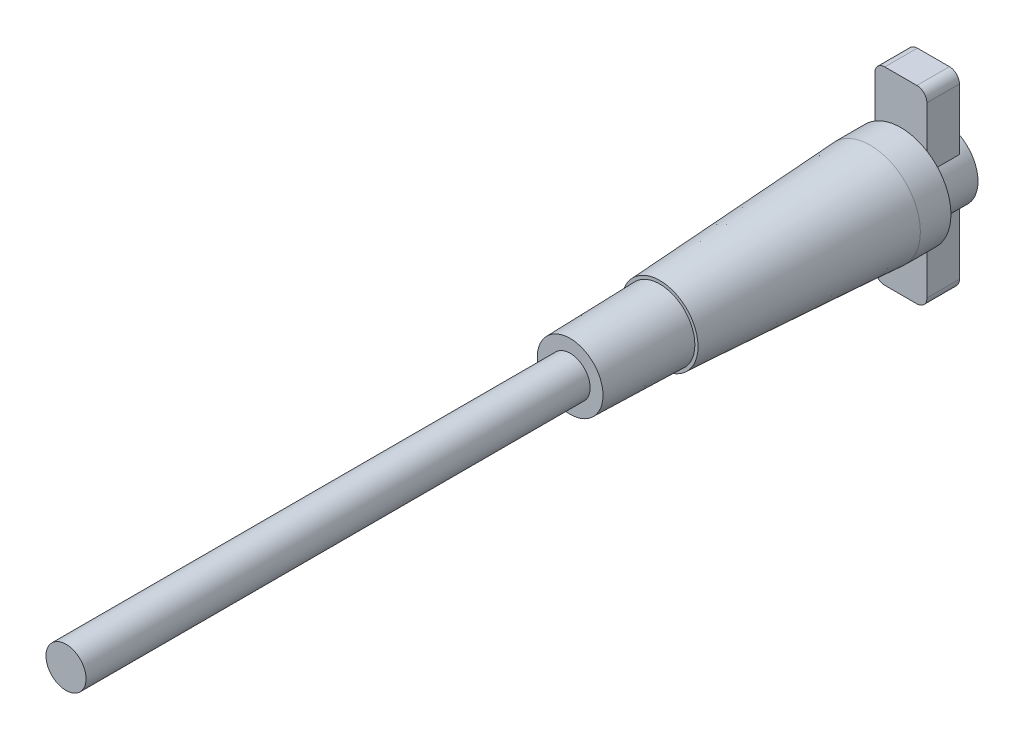
SolidWorks part; units mm, degrees
ref_plane "Front Plane" through (0, 0, 0) normal (0, 0, 1) x (1, 0, 0)
ref_plane "Top Plane" through (0, 0, 0) normal (0, 1, 0) x (1, 0, 0)
ref_plane "Right Plane" through (0, 0, 0) normal (1, 0, 0) x (0, 0, -1)
sketch "Sketch2" plane through (0, 0, 0) normal (1, 0, 0) x (0, 0, -1)
  line L0 (0, 3.556) -> (-4.2672, 3.556)
  line L1 (-4.2672, 3.556) -> (-4.2672, 5.08)
  line L2 (-4.2672, 5.08) -> (-7.366, 5.08)
  line L3 (-7.366, 5.08) -> (-28.702, 3.8735)
  line L4 (-28.702, 3.8735) -> (-28.702, 3.556)
  line L5 (-28.702, 3.556) -> (-37.7952, 3.3337)
  line L6 (-37.7952, 3.3337) -> (-37.7952, 2.032)
  line L7 (-37.7952, 2.032) -> (-88.9, 2.032)
  line L8 (-88.9, 2.032) -> (-88.9, 0)
  line L9 (-88.9, 0) -> (0, 0)
  line L10 (0, 0) -> (0, 3.556)
  point P12 (-46.6451, 2.8937)
  point P13 (-102.8631, 3.8506)
  point P14 (-102.8107, 4.607)
  point P15 (-8.9365, 5.08)
  point P16 (-4.2672, 3.1117)
  dimension "D1" = 4.2672
  dimension "D2" = 5.08
  dimension "D3" = 2.032
  dimension "D4" = 3.3337
  dimension "D5" = 3.556
  dimension "D6" = 3.8735
  dimension "D7" = 28.702
  dimension "D8" = 7.366
  dimension "D9" = 37.7952
  dimension "D10" = 3.556
  dimension "D11" = 88.9
revolve "Revolve1" add sketch "Sketch2" angle 360 about L9
sketch "Sketch3" plane through (0, 0, 4.2672) normal (0, 0, -1) x (-1, 0, 0)
  line L1 (-1.6256, -9.5885) -> (1.6256, -9.5885)
  line L2 (-2.6416, -8.5725) -> (-2.6416, 8.5725)
  line L3 (-1.6256, 9.5885) -> (1.6256, 9.5885)
  line L4 (2.6416, -8.5725) -> (2.6416, 8.5725)
  line L5 (-2.6416, -9.5885) -> (2.6416, 9.5885) construction
  line L6 (-2.6416, 9.5885) -> (2.6416, -9.5885) construction
  arc A0 (1.6256, -9.5885) -> (2.6416, -8.5725) centre (1.6256, -8.5725) ccw
  arc A1 (-1.6256, -9.5885) -> (-2.6416, -8.5725) centre (-1.6256, -8.5725) cw
  arc A2 (1.6256, 9.5885) -> (2.6416, 8.5725) centre (1.6256, 8.5725) cw
  arc A3 (-2.6416, 8.5725) -> (-1.6256, 9.5885) centre (-1.6256, 8.5725) cw
  point P0 (0, 0)
  point P6 (0, 0)
  dimension "D1" = 1.016
  dimension "D2" = 19.177
  dimension "D3" = 5.2832
extrude "Boss-Extrude1" add sketch "Sketch3" along normal blind 3.302
